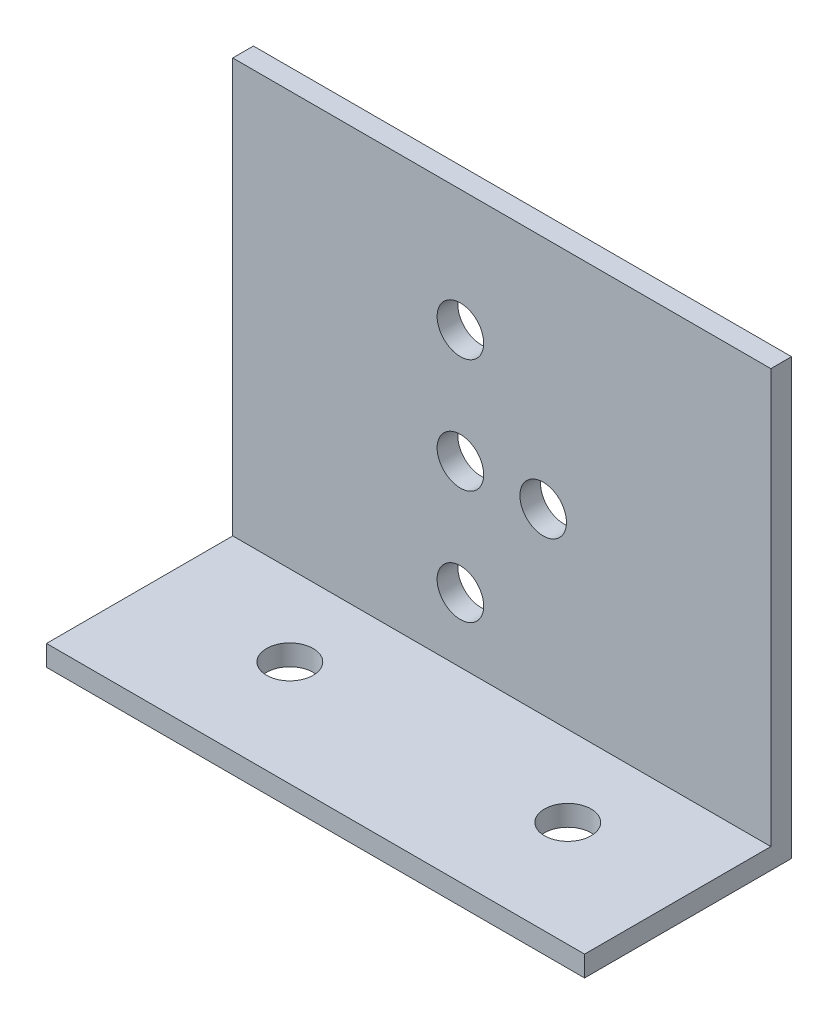
SolidWorks part; units mm, degrees
ref_plane "Plan de face" through (0, 0, 0) normal (0, 0, 1) x (1, 0, 0)
ref_plane "Plan de dessus" through (0, 0, 0) normal (0, 1, 0) x (1, 0, 0)
ref_plane "Plan de droite" through (0, 0, 0) normal (1, 0, 0) x (0, 0, -1)
sketch "Esquisse1" plane through (0, 0, 0) normal (0, 0, 1) x (1, 0, 0)
  line L1 (-26, -21) -> (26, -21)
  line L2 (-26, -21) -> (-26, 21)
  line L3 (-26, 21) -> (26, 21)
  line L4 (26, -21) -> (26, 21)
  line L5 (-26, -21) -> (26, 21) construction
  line L6 (-26, 21) -> (26, -21) construction
  point P0 (0, 0)
  dimension "D1" = 52
  dimension "D2" = 42
extrude "Boss.-Extru.1" add sketch "Esquisse1" along normal blind 20
sketch "Esquisse2" plane through (0, 21, 0) normal (0, 1, 0) x (1, 0, 0)
  line L8 (24, -2) -> (-24, -2)
  line L9 (-24, -2) -> (-24, -18)
  line L10 (-24, -18) -> (24, -18)
  line L11 (24, -18) -> (24, -2)
  line L12 (34.4102, -2) -> (-31.5984, -2)
  line L13 (-31.5984, -2) -> (-31.5984, -42.9462)
  line L14 (-31.5984, -42.9462) -> (34.4102, -42.9462)
  line L15 (34.4102, -42.9462) -> (34.4102, -2)
  dimension "D1" = 2
extrude "Enlèv. mat.-Extru.1" cut sketch "Esquisse2" against normal blind 40
hole_wizard "Dégagement M41" positions "Esquisse4" profile "Esquisse3" hole size "M4" standard "JIS" end condition through all
sketch "Esquisse4" plane through (0, 0, 0) normal (0, 0, -1) x (-1, 0, 0)
  point P0 (4, -12.75)
  point P2 (4, -1.75)
  point P4 (4, 9.25)
  point P6 (-4, -1.75)
sketch "Esquisse3" plane through (-4, -12.75, 0) normal (1, 0, 0) x (0, 1, 0)
  line L0 (0, 0) -> (0, 20)
  line L1 (0, 20) -> (2.25, 20)
  line L2 (2.25, 20) -> (2.25, 0)
  line L5 (2.25, 0) -> (0, 0)
  line L11 (0, -6.35) -> (0, 107.95) construction
  dimension "Diamètre du perçage jusqu'au prochain" = 4.5
  dimension "Profondeur du perçage jusqu'au prochain" = 20
hole_wizard "Dégagement M42" positions "Esquisse7" profile "Esquisse6" hole size "M4" standard "JIS" end condition through all
sketch "Esquisse7" plane through (0, -19, 0) normal (0, 1, 0) x (1, 0, 0)
  point P0 (-12.6957, -9.7851)
  point P2 (14.163, -9.7851)
sketch "Esquisse6" plane through (-12.6957, -19, 9.7851) normal (1, 0, 0) x (0, 0, 1)
  line L0 (0, 0) -> (0, 2)
  line L1 (0, 2) -> (2.25, 2)
  line L2 (2.25, 2) -> (2.25, 0)
  line L5 (2.25, 0) -> (0, 0)
  line L11 (0, -6.35) -> (0, 107.95) construction
  dimension "Diamètre du perçage jusqu'au prochain" = 4.5
  dimension "Profondeur du perçage jusqu'au prochain" = 2
